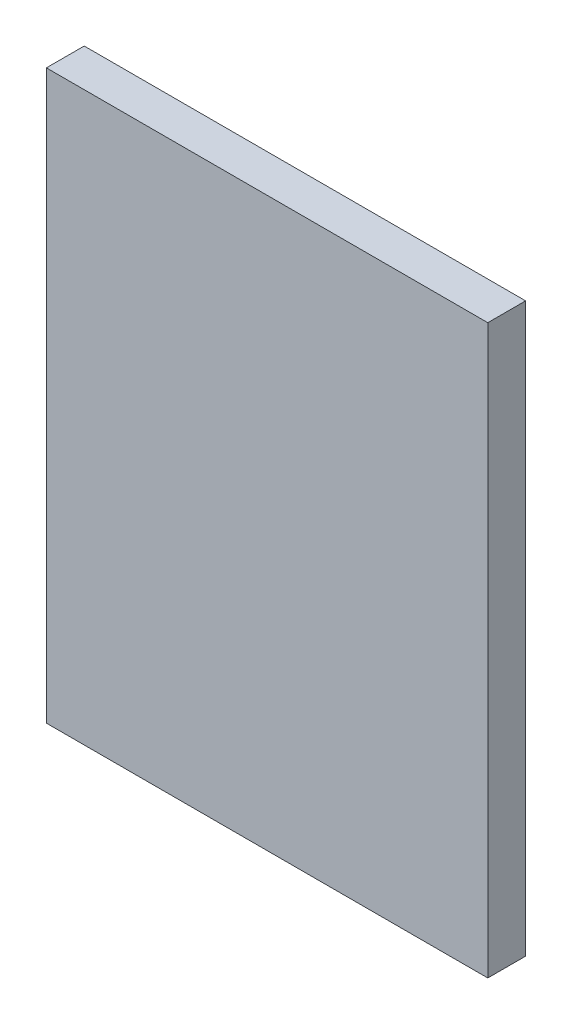
SolidWorks part; units mm, degrees
ref_plane "Front Plane" through (0, 0, 0) normal (0, 0, 1) x (1, 0, 0)
ref_plane "Top Plane" through (0, 0, 0) normal (0, 1, 0) x (1, 0, 0)
ref_plane "Right Plane" through (0, 0, 0) normal (1, 0, 0) x (0, 0, -1)
sketch "Sketch1" plane through (0, 0, 0) normal (0, 0, 1) x (1, 0, 0)
  line L1 (17.5, 22.5) -> (-17.5, 22.5)
  line L2 (17.5, 22.5) -> (17.5, -22.5)
  line L3 (17.5, -22.5) -> (-17.5, -22.5)
  line L4 (-17.5, 22.5) -> (-17.5, -22.5)
  line L5 (17.5, 22.5) -> (-17.5, -22.5) construction
  line L6 (17.5, -22.5) -> (-17.5, 22.5) construction
  point P0 (0, 0)
  dimension "D1" = 45
  dimension "D2" = 35
extrude "Boss-Extrude1" add sketch "Sketch1" along normal blind 3
